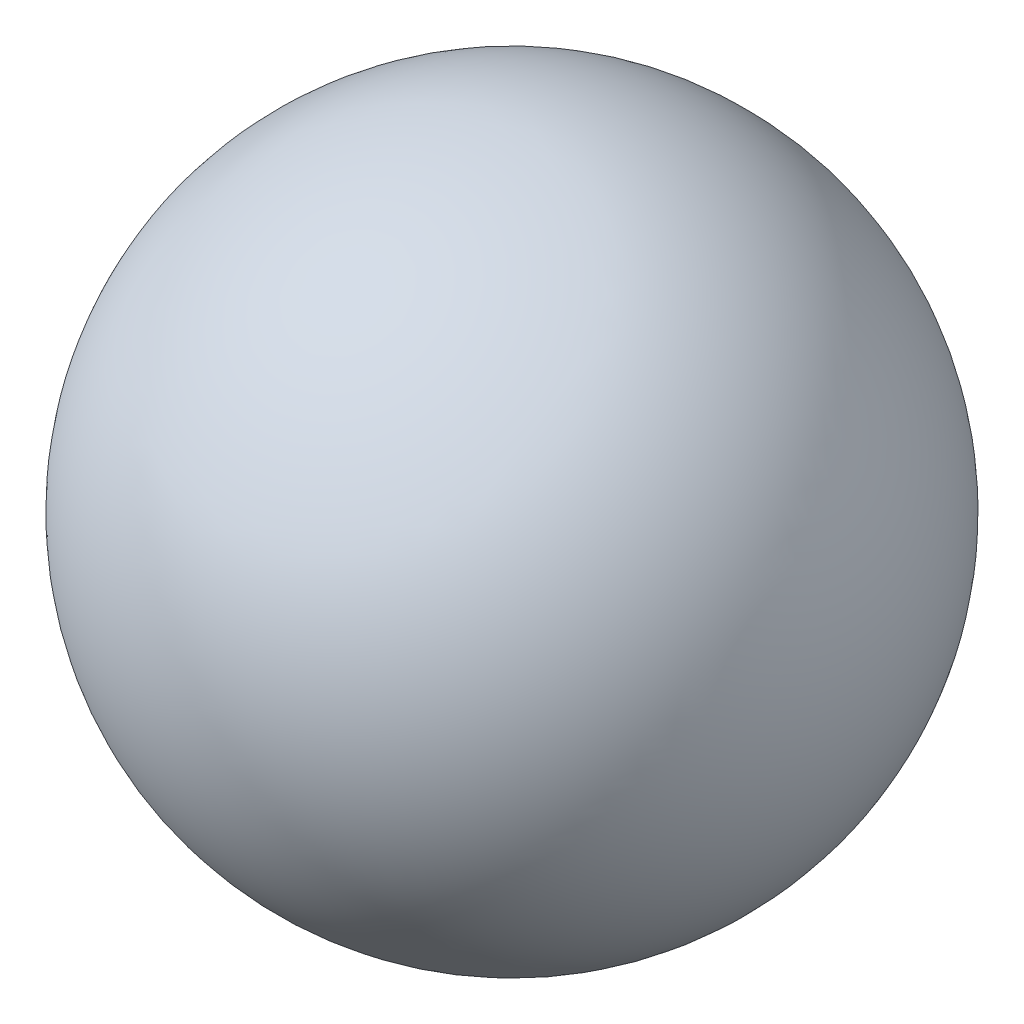
SolidWorks part; units mm, degrees
ref_plane "Front Plane" through (0, 0, 0) normal (0, 0, 1) x (1, 0, 0)
ref_plane "Top Plane" through (0, 0, 0) normal (0, 1, 0) x (1, 0, 0)
ref_plane "Right Plane" through (0, 0, 0) normal (1, 0, 0) x (0, 0, -1)
ref_plane "Plane1" through (0, 0, 0) normal (0, 0, 1) x (1, 0, 0)
sketch "Sketch1" plane through (0, 0, 0) normal (0, 0, 1) x (1, 0, 0)
  line L0 (2.794, 2.97) -> (1.206, 2.97)
  line L1 (2.794, 2.97) -> (1.206, 2.97) construction
  arc A0 (1.206, 2.97) -> (2.794, 2.97) centre (2, 2.97) cw
revolve "Revolve1" add sketch "Sketch1" angle 360 about L1
